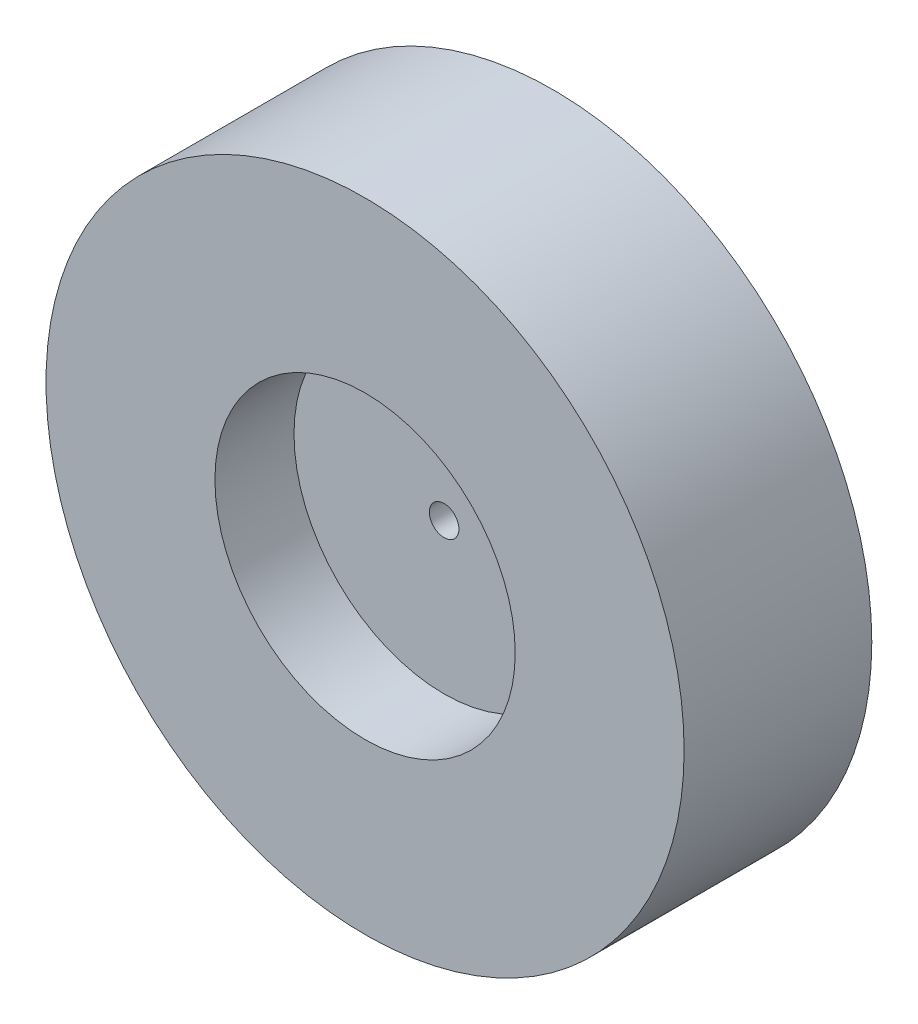
SolidWorks part; units mm, degrees
ref_plane "Front Plane" through (0, 0, 0) normal (0, 0, 1) x (1, 0, 0)
ref_plane "Top Plane" through (0, 0, 0) normal (0, 1, 0) x (1, 0, 0)
ref_plane "Right Plane" through (0, 0, 0) normal (1, 0, 0) x (0, 0, -1)
sketch "Sketch1" plane through (0, 0, 0) normal (0, 0, 1) x (1, 0, 0)
  circle A0 centre (0, 0) radius 107.95
  circle A1 centre (0, 0) radius 50.8
  dimension "D1" = 215.9
  dimension "D2" = 101.6
extrude "Boss-Extrude1" add sketch "Sketch1" along normal mid plane 63.5
sketch "Sketch2" plane through (0, 0, 0) normal (0, 0, 1) x (1, 0, 0)
  circle A0 centre (0, 0) radius 5
  circle A1 centre (0, 0) radius 50.8 construction
  circle A2 centre (0, 0) radius 50.8
  dimension "D1" = 10
extrude "Boss-Extrude2" add sketch "Sketch2" along normal mid plane 10
